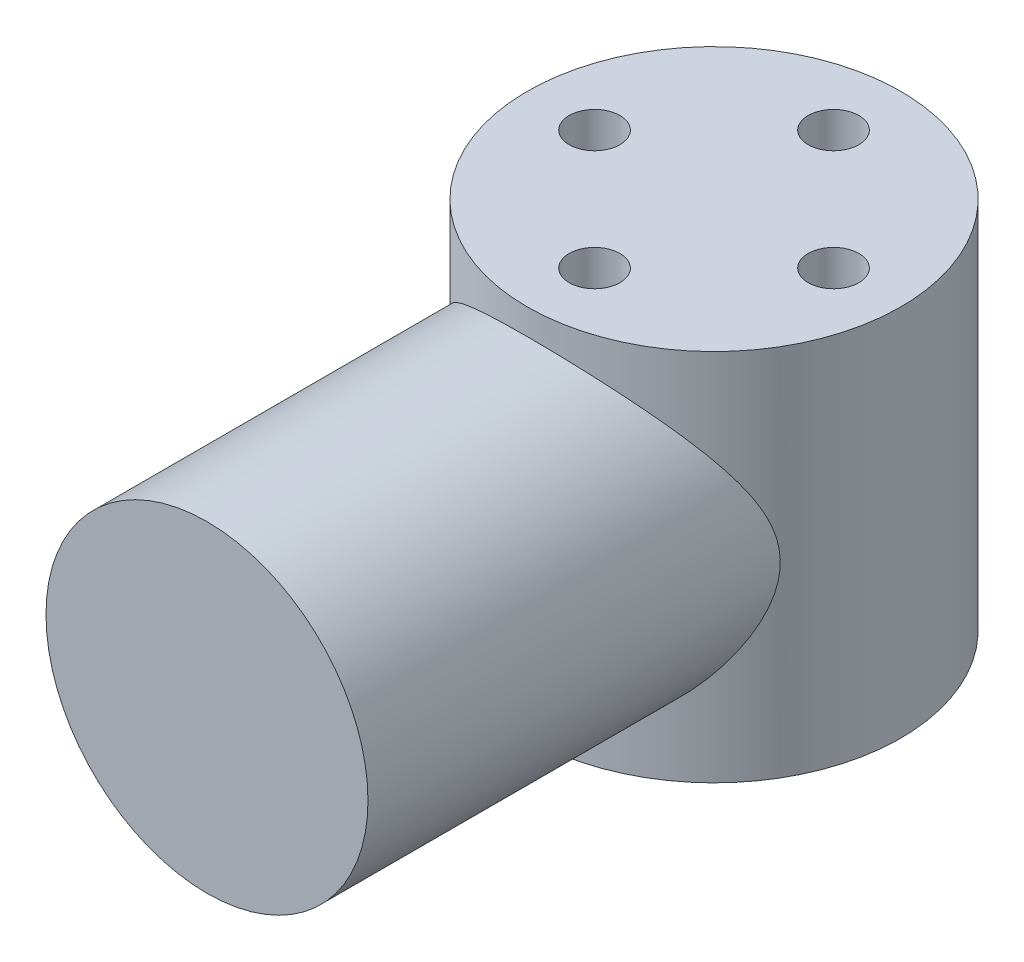
SolidWorks part; units mm, degrees
material "ABS"
ref_plane "Front Plane" through (0, 0, 0) normal (0, 0, 1) x (1, 0, 0)
ref_plane "Top Plane" through (0, 0, 0) normal (0, 1, 0) x (1, 0, 0)
ref_plane "Right Plane" through (0, 0, 0) normal (1, 0, 0) x (0, 0, -1)
sketch "Sketch1" plane through (0, 0, 0) normal (0, 1, 0) x (1, 0, 0)
  circle A0 centre (0, 0) radius 11.05
  circle A1 centre (0, 0) radius 7.07 construction
  point P4 (0, 7.07)
  point P5 (7.07, 0)
  point P6 (0, -7.07)
  point P7 (-7.07, 0)
  dimension "D1" = 14.14
  dimension "D2" = 22.1
extrude "Boss-Extrude1" add sketch "Sketch1" along normal blind 22.1
sketch "Sketch4" plane through (0, 0, 0) normal (0, 0, 1) x (1, 0, 0)
  line L0 (0, 22.1) -> (0, 0) construction
  line L1 (11.05, 22.1) -> (-11.05, 22.1) construction
  circle A0 centre (0, 11.05) radius 9.525
  dimension "D1" = 19.05
extrude "Boss-Extrude3" add sketch "Sketch4" along normal blind 30
hole_wizard "Ø3.0mm Dowel Hole1" positions "Sketch6" profile "Sketch7" hole size "Ø3.0" standard "ANSI Metric" end condition through all
sketch "Sketch6" plane through (0, 0, 0) normal (0, -1, 0) x (-1, 0, 0)
  point P0 (7.07, 0)
  point P3 (0, 7.07)
  point P6 (-7.07, 0)
  point P9 (0, -7.07)
sketch "Sketch7" plane through (-7.07, 0, 0) normal (1, 0, 0) x (0, 0, -1)
  line L0 (0, 0) -> (0, 22.1)
  line L1 (0, 22.1) -> (1.5, 22.1)
  line L2 (1.5, 22.1) -> (1.5, 0)
  line L5 (1.5, 0) -> (0, 0)
  line L11 (0, -6.35) -> (0, 107.95) construction
  dimension "Thru Hole Dia." = 3
  dimension "Thru Hole Depth" = 22.1
